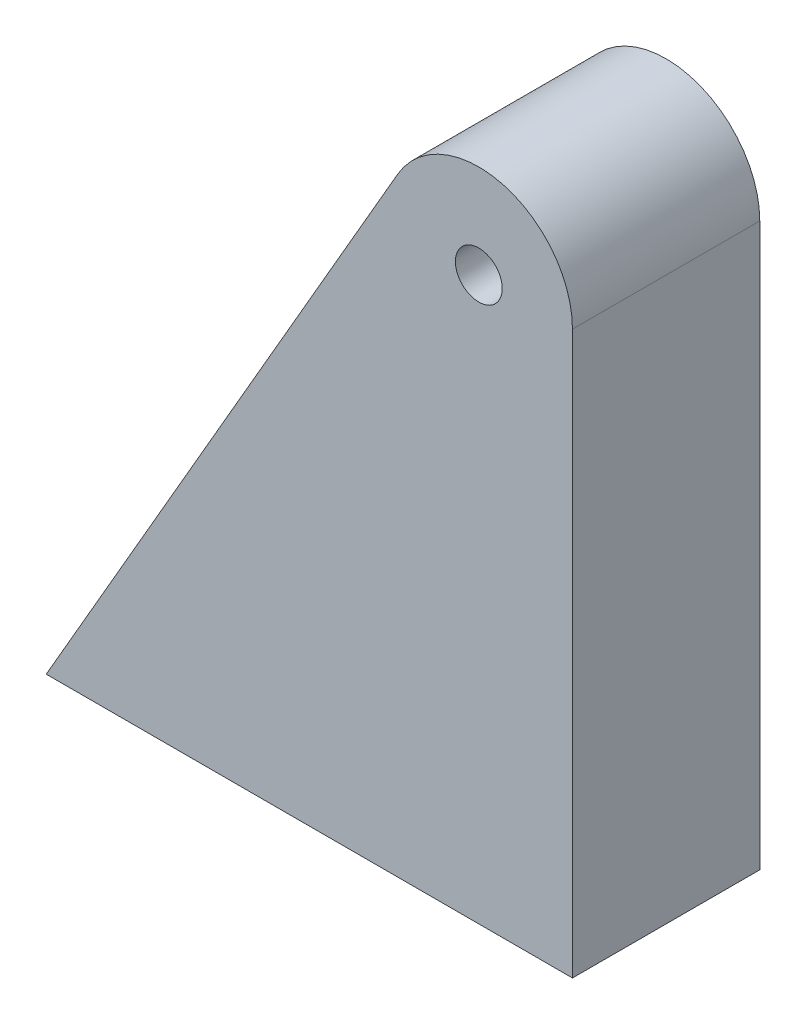
SolidWorks part; units mm, degrees
ref_plane "Front Plane" through (0, 0, 0) normal (0, 0, 1) x (1, 0, 0)
ref_plane "Top Plane" through (0, 0, 0) normal (0, 1, 0) x (1, 0, 0)
ref_plane "Right Plane" through (0, 0, 0) normal (1, 0, 0) x (0, 0, -1)
sketch "Sketch1" plane through (0, 0, 0) normal (0, 0, 1) x (1, 0, 0)
  line L0 (0, 0) -> (23.8301, 41.275)
  line L1 (0, 0) -> (35.6794, 0)
  line L2 (35.6794, 0) -> (35.6794, 38.1)
  arc A0 (35.6794, 38.1) -> (23.8301, 41.275) centre (29.3294, 38.1) ccw
  circle A1 centre (29.3294, 38.1) radius 1.5875
  dimension "D1" = 6.35
  dimension "D4" = 3.175
  dimension "D2" = 38.1
  dimension "D3" = 60
extrude "Boss-Extrude1" add sketch "Sketch1" along normal blind 12.7
